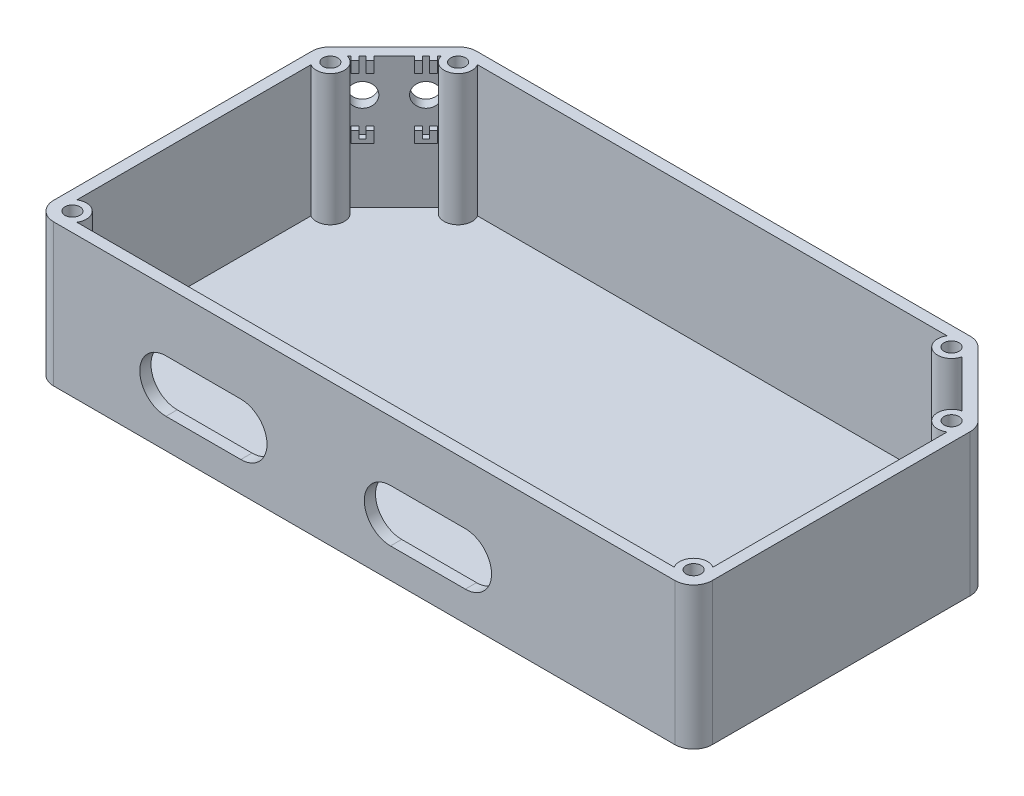
SolidWorks part; units mm, degrees
ref_plane "Front Plane" through (0, 0, 0) normal (0, 0, 1) x (1, 0, 0)
ref_plane "Top Plane" through (0, 0, 0) normal (0, 1, 0) x (1, 0, 0)
ref_plane "Right Plane" through (0, 0, 0) normal (1, 0, 0) x (0, 0, -1)
sketch "Sketch1" plane through (0, 0, 0) normal (0, 1, 0) x (1, 0, 0)
  line L0 (-88, 28) -> (-68, 48)
  line L1 (88, -48) -> (-88, -48)
  line L2 (88, -48) -> (88, 48)
  line L3 (88, 48) -> (-88, 48)
  line L4 (-88, -48) -> (-88, 48)
  line L5 (88, -48) -> (-88, 48) construction
  line L6 (88, 48) -> (-88, -48) construction
  line L7 (0, 48) -> (0, -48) construction
  line L8 (88, 28) -> (68, 48)
  point P0 (0, 0)
  dimension "D1" = 176
  dimension "D2" = 96
  dimension "D3" = 20
  dimension "D4" = 20
extrude "Boss-Extrude1" add sketch "Sketch1" along normal blind 3 contours L2 L8 L3 L0 L4 L1
sketch "Sketch2" plane through (0, 3, 0) normal (0, 1, 0) x (1, 0, 0)
  line L6 (88, 28) -> (68, 48) construction
  line L7 (88, -48) -> (88, 28) construction
  line L8 (88, -48) -> (-88, -48) construction
  line L9 (-88, -48) -> (-88, 28) construction
  line L10 (68, 48) -> (-68, 48) construction
  line L11 (-88, 28) -> (-68, 48) construction
  line L12 (85, -45) -> (85, 26.7574)
  line L13 (85, 26.7574) -> (66.7574, 45)
  line L14 (66.7574, 45) -> (-66.7574, 45)
  line L15 (-66.7574, 45) -> (-85, 26.7574)
  line L16 (-85, 26.7574) -> (-85, -45)
  line L17 (-85, -45) -> (85, -45)
  line L18 (85, -45) -> (85, 26.7574)
  line L19 (85, 26.7574) -> (66.7574, 45)
  line L20 (66.7574, 45) -> (-66.7574, 45)
  line L21 (-66.7574, 45) -> (-85, 26.7574)
  line L22 (-85, 26.7574) -> (-85, -45)
  line L23 (-85, -45) -> (85, -45)
  line L24 (88, 28) -> (68, 48)
  line L25 (88, -48) -> (88, 28)
  line L26 (88, -48) -> (-88, -48)
  line L27 (-88, -48) -> (-88, 28)
  line L28 (68, 48) -> (-68, 48)
  line L29 (-88, 28) -> (-68, 48)
  dimension "D1" = 3
extrude "Boss-Extrude2" add sketch "Sketch2" along normal blind 35
sketch "Sketch3" plane through (-58, 0, -58) normal (-0.7071, 0, -0.7071) x (-0.7071, 0, 0.7071)
  line L0 (28.2843, 38) -> (28.2843, 0) construction
  line L1 (14.1421, 38) -> (42.4264, 38) construction
  line L2 (42.4264, 0) -> (14.1421, 0) construction
  line L3 (28.2843, 29) -> (34.2843, 29) construction
  line L4 (28.2843, 29) -> (22.2843, 29) construction
  circle A0 centre (34.2843, 29) radius 3.1
  circle A1 centre (22.2843, 29) radius 3.1
  dimension "D1" = 6.2
  dimension "D4" = 6
  dimension "D2" = 6
  dimension "D3" = 9
  dimension "D5" = 9
extrude "Cut-Extrude1" cut sketch "Sketch3" against normal blind 10
sketch "Sketch4" plane through (-55.8787, 0, -55.8787) normal (0.7071, 0, 0.7071) x (0.7071, 0, -0.7071)
  line L0 (-22.2843, 38) -> (-22.2843, 3)
  line L1 (-15.3848, 38) -> (-41.1838, 38) construction
  line L2 (-15.3848, 3) -> (-41.1838, 3) construction
  line L3 (-25.3843, 29) -> (-19.1843, 29) construction
  line L4 (-24.4843, 38) -> (-24.4843, 35)
  line L5 (-24.4843, 35) -> (-22.9843, 35)
  line L6 (-22.9843, 35) -> (-22.9843, 38)
  line L7 (-22.9843, 38) -> (-24.4843, 38)
  line L8 (-21.5843, 35) -> (-21.5843, 38)
  line L9 (-20.0843, 35) -> (-21.5843, 35)
  line L10 (-20.0843, 38) -> (-20.0843, 35)
  line L11 (-21.5843, 38) -> (-20.0843, 38)
  line L12 (-24.4843, 21.8) -> (-22.9843, 21.8)
  line L13 (-22.9843, 21.8) -> (-22.9843, 19.8)
  line L14 (-22.9843, 19.8) -> (-21.5843, 19.8)
  line L15 (-22.2843, 19.8) -> (-22.2843, 18.8)
  line L16 (-20.0843, 18.8) -> (-24.4843, 18.8)
  line L17 (-24.4843, 18.8) -> (-24.4843, 21.8)
  line L18 (-21.5843, 21.8) -> (-21.5843, 19.8)
  line L19 (-20.0843, 18.8) -> (-20.0843, 21.8)
  line L20 (-20.0843, 21.8) -> (-21.5843, 21.8)
  line L21 (-28.2843, 38) -> (-28.2843, 32.6874) construction
  line L22 (-33.5843, 21.8) -> (-33.5843, 19.8)
  line L23 (-33.5843, 19.8) -> (-34.9843, 19.8)
  line L24 (-34.9843, 21.8) -> (-34.9843, 19.8)
  line L25 (-36.4843, 21.8) -> (-34.9843, 21.8)
  line L26 (-36.4843, 18.8) -> (-36.4843, 21.8)
  line L27 (-36.4843, 18.8) -> (-32.0843, 18.8)
  line L28 (-32.0843, 18.8) -> (-32.0843, 21.8)
  line L29 (-32.0843, 21.8) -> (-33.5843, 21.8)
  line L30 (-36.4843, 38) -> (-36.4843, 35)
  line L31 (-34.9843, 38) -> (-36.4843, 38)
  line L32 (-34.9843, 35) -> (-34.9843, 38)
  line L33 (-36.4843, 35) -> (-34.9843, 35)
  line L34 (-32.0843, 35) -> (-33.5843, 35)
  line L35 (-33.5843, 35) -> (-33.5843, 38)
  line L36 (-33.5843, 38) -> (-32.0843, 38)
  line L37 (-32.0843, 38) -> (-32.0843, 35)
  circle A0 centre (-22.2843, 29) radius 3.1 construction
  point P11 (-22.2843, 29)
  point P14 (-23.7343, 35)
  line M11 (-15.3848, 38) -> (-41.1838, 38)
  dimension "D1" = 0.7
  dimension "D2" = 1.5
  dimension "D3" = 6
  dimension "D4" = 3
  dimension "D5" = 2
  dimension "D6" = 1.5
  dimension "D7" = 18.2
  dimension "D8" = 0.7
extrude "Boss-Extrude3" add sketch "Sketch4" along normal blind 1.5 contours L10 L8 L9 M11 | L17 L16 L0 L14 L13 L12 | L19 L20 L18 L14 L0 L16 | L28 L29 L22 L23 L24 L25 L26 L27 | L30 L33 L32 M11 | L6 L7 L4 L5 | L37 L34 L35 L36
sketch "Sketch6" plane through (0, 3, 0) normal (0, 1, 0) x (1, 0, 0)
  line L0 (68, 48) -> (-68, 48) construction
  line L1 (-83, 25.9289) -> (-65.9289, 43) construction
  line L2 (-68, 48) -> (-88, 28) construction
  line L3 (-88, 28) -> (-88, -48) construction
  line L5 (-88, -48) -> (88, -48) construction
  line L6 (88, -48) -> (88, 28) construction
  line L7 (65.9289, 43) -> (83, 25.9289) construction
  line L8 (88, 28) -> (68, 48) construction
  circle A0 centre (-65.9289, 43) radius 3.75
  circle A1 centre (65.9289, 43) radius 3.75
  circle A2 centre (83, 25.9289) radius 3.75
  circle A3 centre (83, -43) radius 3.75
  circle A4 centre (-83, -43) radius 3.75
  circle A5 centre (-83, 25.9289) radius 3.75
  dimension "D11" = 7.5
  dimension "D1" = 5
  dimension "D2" = 5
  dimension "D3" = 5
  dimension "D4" = 5
  dimension "D5" = 5
  dimension "D6" = 5
  dimension "D7" = 5
  dimension "D8" = 5
  dimension "D9" = 5
  dimension "D10" = 5
extrude "Boss-Extrude4" add sketch "Sketch6" along normal blind 35
sketch "Sketch7" plane through (0, 38, 0) normal (0, 1, 0) x (1, 0, 0)
  circle A0 centre (-65.9289, 43) radius 2
  circle A1 centre (-83, 25.9289) radius 2
  circle A2 centre (-83, -43) radius 2
  circle A3 centre (83, -43) radius 2
  circle A4 centre (83, 25.9289) radius 2
  circle A5 centre (65.9289, 43) radius 2
  dimension "D1" = 4
extrude "Cut-Extrude2" cut sketch "Sketch7" against normal blind 38
sketch "Sketch8" plane through (0, 0, 0) normal (0, -1, 0) x (1, 0, 0)
  circle A0 centre (-83, 43) radius 2.6
  circle A1 centre (83, 43) radius 2.6
  circle A2 centre (83, -25.9289) radius 2.6
  circle A3 centre (65.9289, -43) radius 2.6
  circle A4 centre (-65.9289, -43) radius 2.6
  circle A5 centre (-83, -25.9289) radius 2.6
  dimension "D1" = 5.2
extrude "Cut-Extrude3" cut sketch "Sketch8" against normal blind 25
sketch "Sketch9" plane through (0, 0, 48) normal (0, 0, 1) x (1, 0, 0)
  line L0 (-88, 15) -> (88, 15) construction
  line L1 (-88, 38) -> (-88, 0) construction
  line L2 (88, 38) -> (88, 0) construction
  line L3 (-33, 15) -> (-53, 15) construction
  line L4 (-33, 8) -> (-53, 8)
  line L5 (-33, 22) -> (-53, 22)
  line L6 (88, 0) -> (-88, 0) construction
  line L7 (27, 15) -> (7, 15) construction
  line L8 (27, 8) -> (7, 8)
  line L9 (27, 22) -> (7, 22)
  arc A0 (-33, 8) -> (-33, 22) centre (-33, 15) ccw
  arc A1 (-53, 22) -> (-53, 8) centre (-53, 15) ccw
  arc A2 (27, 8) -> (27, 22) centre (27, 15) ccw
  arc A3 (7, 22) -> (7, 8) centre (7, 15) ccw
  point P8 (-43, 15)
  point P17 (17, 15)
  dimension "D4" = 7
  dimension "D1" = 15
  dimension "D2" = 45
  dimension "D3" = 20
  dimension "D5" = 60
  dimension "D6" = 20
extrude "Cut-Extrude4" cut sketch "Sketch9" against normal blind 3
fillet "Fillet1" radius 5 6 edges at (88, 19, 48) (88, 19, -28) (68, 19, -48) (-68, 19, -48) (-88, 19, -28) (-88, 19, 48)
